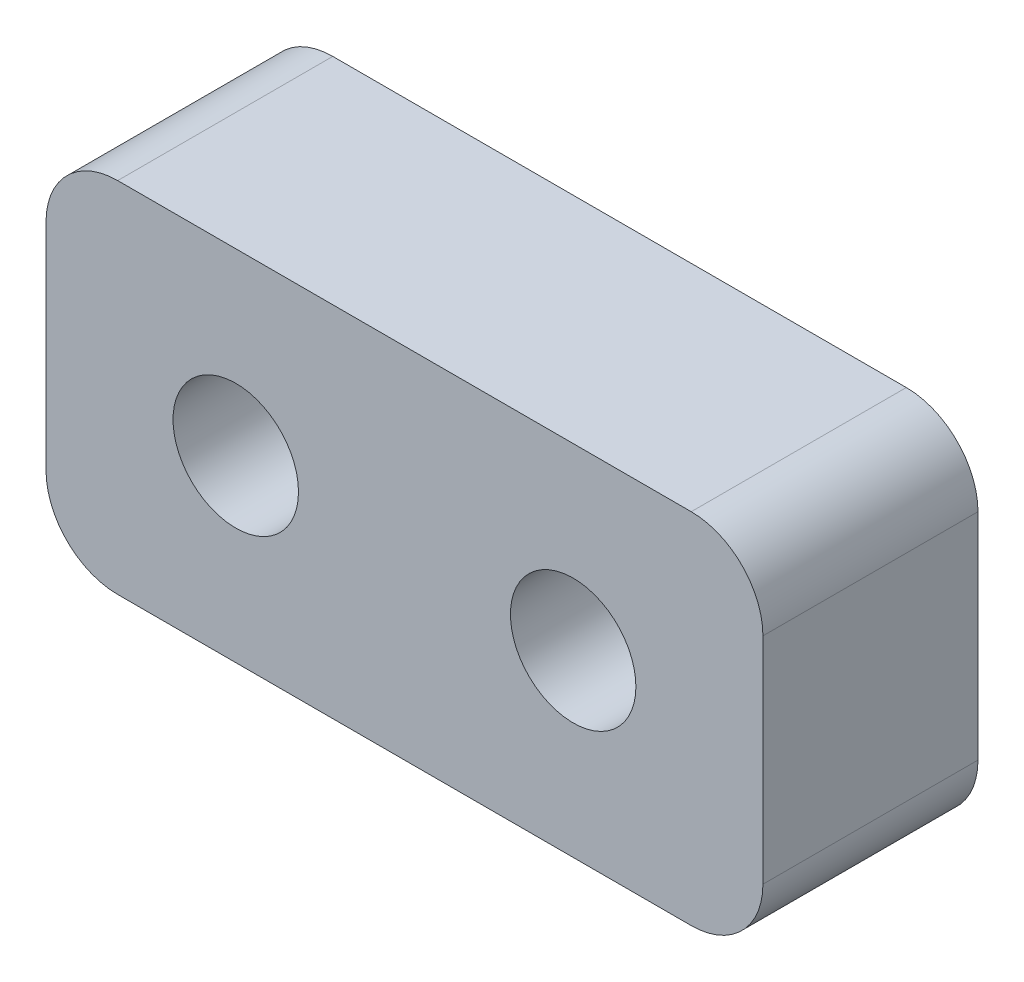
SolidWorks part; units mm, degrees
ref_plane "Alzado" through (0, 0, 0) normal (0, 0, 1) x (1, 0, 0)
ref_plane "Planta" through (0, 0, 0) normal (0, 1, 0) x (1, 0, 0)
ref_plane "Vista lateral" through (0, 0, 0) normal (1, 0, 0) x (0, 0, -1)
sketch "Croquis1" plane through (0, 0, 0) normal (0, 0, 1) x (1, 0, 0)
  line L1 (-20, 10) -> (20, 10)
  line L2 (-20, 10) -> (-20, -10)
  line L3 (-20, -10) -> (20, -10)
  line L4 (20, 10) -> (20, -10)
  line L5 (-20, 10) -> (20, -10) construction
  line L6 (-20, -10) -> (20, 10) construction
  point P0 (0, 0)
  dimension "D1" = 40
  dimension "D2" = 20
extrude "Saliente-Extruir1" add sketch "Croquis1" along normal blind 12
fillet "Redondeo1" radius 4 4 edges at (-20, -10, 6) (20, -10, 6) (20, 10, 6) (-20, 10, 6)
sketch "Croquis2" plane through (0, 0, 0) normal (0, 0, -1) x (-1, 0, 0)
  circle A0 centre (0, 0) radius 2.5
  dimension "D1" = 5
extrude "Cortar-Extruir1" cut sketch "Croquis2" against normal blind 8
sketch "Croquis3" plane through (0, 0, 12) normal (0, 0, 1) x (1, 0, 0)
  line L0 (0, 0) -> (-9.4127, 0) construction
  line L1 (0, 0) -> (9.4127, 0) construction
  circle A0 centre (-9.4127, 0) radius 3.5
  circle A1 centre (9.4127, 0) radius 3.5
  dimension "D1" = 7
extrude "Cortar-Extruir2" cut sketch "Croquis3" against normal offset from surface (10 mm away) 2 up to face at (-2.5, 0, 0)
sketch "Croquis4" plane through (0, 0, 2) normal (0, 0, 1) x (1, 0, 0)
  line L0 (-9.4127, 0) -> (0, 0) construction
  line L1 (0, 0) -> (9.4127, 0) construction
  circle A0 centre (-9.4127, 0) radius 2
  circle A1 centre (9.4127, 0) radius 2
  dimension "D1" = 4
extrude "Cortar-Extruir3" cut sketch "Croquis4" against normal up to surface (2 mm away) up to face at (-2.5, 0, 0)
